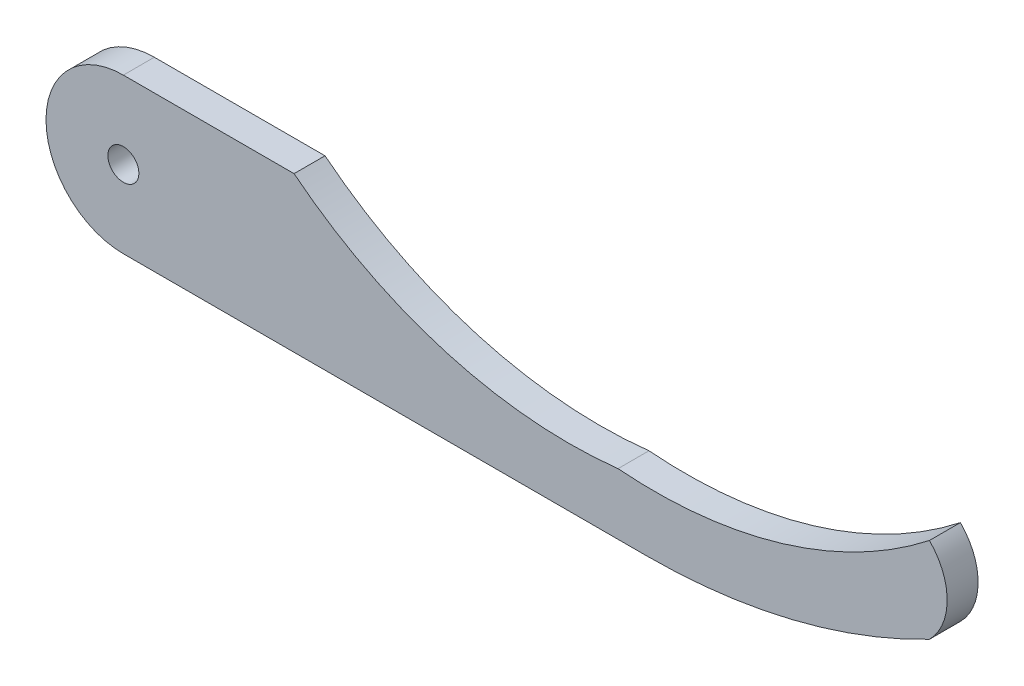
SolidWorks part; units mm, degrees
material "6063-O"
ref_plane "Ön Düzlem" through (0, 0, 0) normal (0, 0, 1) x (1, 0, 0)
ref_plane "Üst Düzlem" through (0, 0, 0) normal (0, 1, 0) x (1, 0, 0)
ref_plane "Sağ Düzlem" through (0, 0, 0) normal (1, 0, 0) x (0, 0, -1)
sketch "Çizim1" plane through (0, 0, 0) normal (0, 0, 1) x (1, 0, 0)
  line L0 (-50, 7.5) -> (-33.4533, 7.5)
  line L3 (-50, -7.5) -> (0.7077, -7.5)
  arc A2 (-50, 7.5) -> (-50, -7.5) centre (-50, 0) ccw
  arc A4 (-33.4533, 7.5) -> (-2.0482, -1.5616) centre (-6.7868, 40.9675) ccw
  arc A5 (-2.0482, -1.5616) -> (28.1383, 7.5) centre (1.4864, 41.474) ccw
  arc A6 (0.7077, -7.5) -> (28.1383, -0.7963) centre (0.7077, 51.9731) ccw
  arc A7 (28.1383, -0.7963) -> (28.1383, 7.5) centre (23.9901, 3.3518) ccw
  point P3 (-7.5, 0)
extrude "Yükseklik-Ekstrüzyon1" add sketch "Çizim1" along normal blind 3
sketch "Çizim2" plane through (0, 0, 3) normal (0, 0, 1) x (1, 0, 0)
  circle A2 centre (-50, 0) radius 1.5
  dimension "D1" = 3
extrude "Kes-Ekstrüzyon1" cut sketch "Çizim2" against normal blind 12.5
